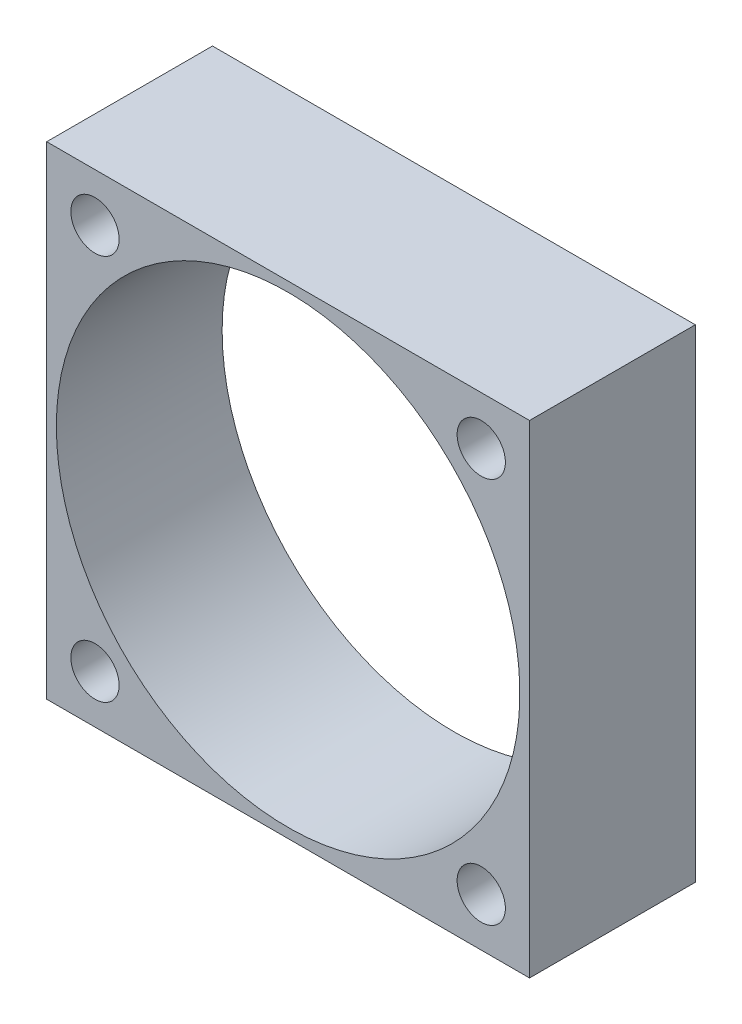
SolidWorks part; units mm, degrees
ref_plane "前视基准面" through (0, 0, 0) normal (0, 0, 1) x (1, 0, 0)
ref_plane "上视基准面" through (0, 0, 0) normal (0, 1, 0) x (1, 0, 0)
ref_plane "右视基准面" through (0, 0, 0) normal (1, 0, 0) x (0, 0, -1)
sketch "草图1" plane through (0, 0, 0) normal (0, 0, 1) x (1, 0, 0)
  line L1 (-15, -15) -> (15, -15)
  line L2 (-15, -15) -> (-15, 15)
  line L3 (-15, 15) -> (15, 15)
  line L4 (15, -15) -> (15, 15)
  line L5 (-15, -15) -> (15, 15) construction
  line L6 (-15, 15) -> (15, -15) construction
  circle A0 centre (0, 0) radius 14.4
  circle A3 centre (-12, 12) radius 1.5
  circle A5 centre (12, 12) radius 1.5
  circle A6 centre (12, -12) radius 1.5
  circle A7 centre (-12, -12) radius 1.5
  point P17 (0, 0)
  dimension "D1" = 28.8
  dimension "D3" = 3
  dimension "D2" = 30
  dimension "D5" = 24
  dimension "D4" = 4
extrude "凸台-拉伸1" add sketch "草图1" along normal blind 10.3
